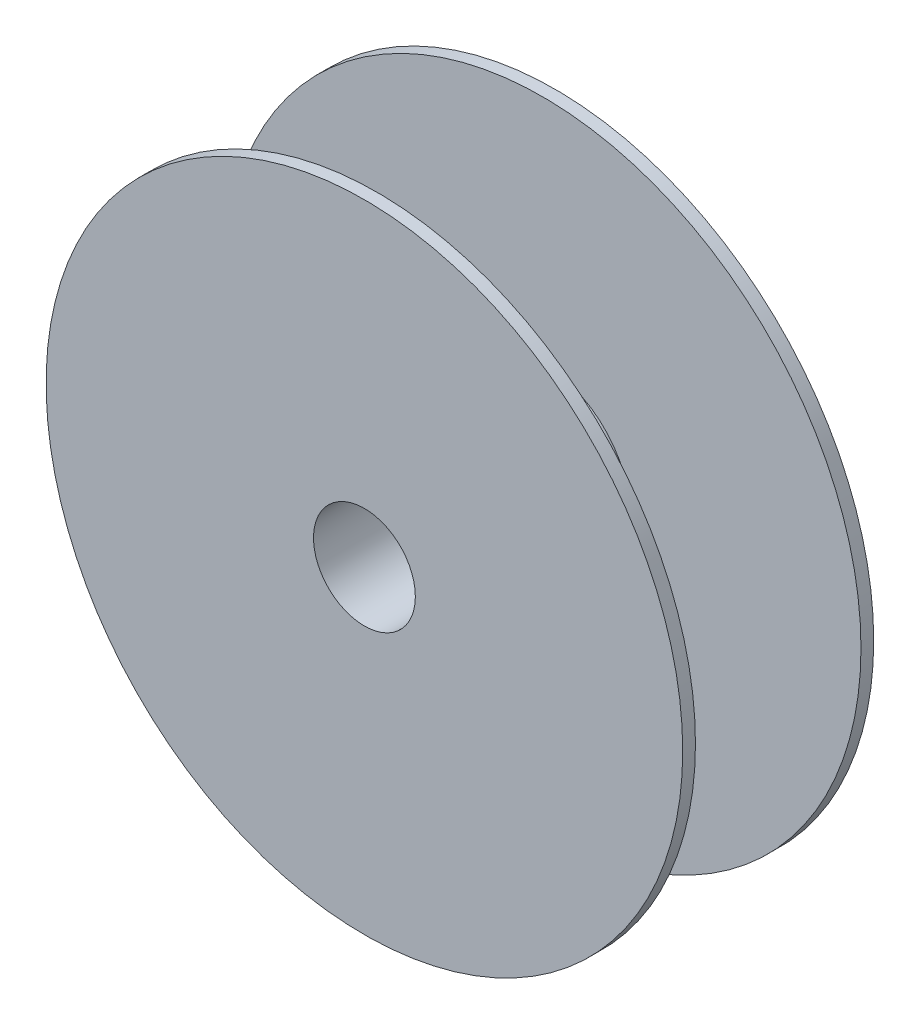
SolidWorks part; units mm, degrees
ref_plane "Front Plane" through (0, 0, 0) normal (0, 0, 1) x (1, 0, 0)
ref_plane "Top Plane" through (0, 0, 0) normal (0, 1, 0) x (1, 0, 0)
ref_plane "Right Plane" through (0, 0, 0) normal (1, 0, 0) x (0, 0, -1)
sketch "Sketch1" plane through (0, 0, 0) normal (0, 0, 1) x (1, 0, 0)
  circle A0 centre (0, 0) radius 26.25
  circle A1 centre (0, 0) radius 16
  circle A2 centre (0, 0) radius 100
  dimension "D1" = 200
  dimension "D2" = 32
  dimension "D3" = 52.5
extrude "Boss-Extrude1" add sketch "Sketch1" along normal mid plane 60 contours A2 A0 | A0 A1
sketch "Sketch2" plane through (0, 0, 0) normal (0, 0, 1) x (1, 0, 0)
  circle A0 centre (0, 0) radius 27.5
  circle A1 centre (0, 0) radius 100
  dimension "D1" = 200
  dimension "D2" = 55
extrude "Cut-Extrude1" cut sketch "Sketch2" against normal mid plane 52
